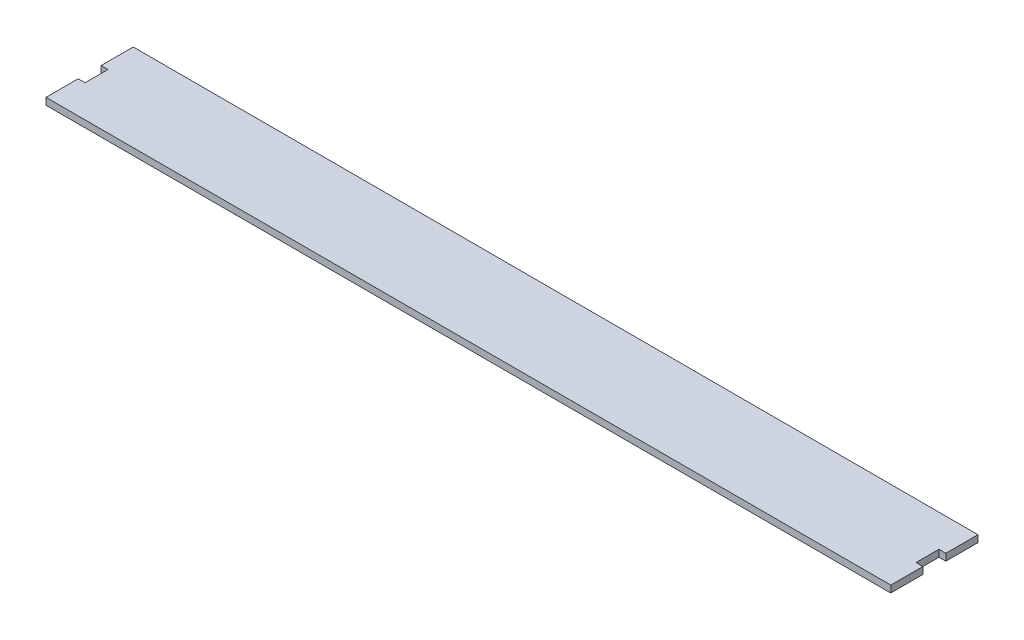
SolidWorks part; units mm, degrees
ref_plane "Front Plane" through (0, 0, 0) normal (0, 0, 1) x (1, 0, 0)
ref_plane "Top Plane" through (0, 0, 0) normal (0, 1, 0) x (1, 0, 0)
ref_plane "Right Plane" through (0, 0, 0) normal (1, 0, 0) x (0, 0, -1)
sketch "Sketch1" plane through (0, 0, 0) normal (0, 1, 0) x (1, 0, 0)
  line L1 (184, 19) -> (-184, 19)
  line L2 (184, 19) -> (184, 5)
  line L3 (184, -19) -> (-184, -19)
  line L4 (-184, 19) -> (-184, 5)
  line L5 (184, 19) -> (-184, -19) construction
  line L6 (184, -19) -> (-184, 19) construction
  line L7 (-181, 5) -> (-181, -5)
  line L8 (-181, 5) -> (-184, 5)
  line L9 (-181, -5) -> (-184, -5)
  line L10 (-184, -5) -> (-184, -19)
  line L11 (181, 5) -> (181, -5)
  line L12 (181, 5) -> (184, 5)
  line L13 (181, -5) -> (184, -5)
  line L14 (184, -5) -> (184, -19)
  point P0 (0, 0)
  dimension "D1" = 368
  dimension "D2" = 38
  dimension "D3" = 3
  dimension "D4" = 10
  dimension "D5" = 3
  dimension "D6" = 10
extrude "Boss-Extrude1" add sketch "Sketch1" along normal blind 3
